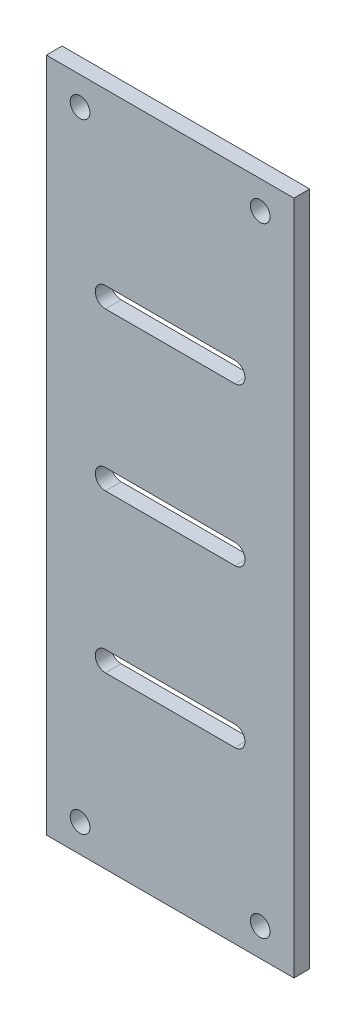
SolidWorks part; units mm, degrees
ref_plane "Front Plane" through (0, 0, 0) normal (0, 0, 1) x (1, 0, 0)
ref_plane "Top Plane" through (0, 0, 0) normal (0, 1, 0) x (1, 0, 0)
ref_plane "Right Plane" through (0, 0, 0) normal (1, 0, 0) x (0, 0, -1)
sketch "Pack access with strap ventilation profile" plane through (0, 0, 0) normal (0, 0, 1) x (1, 0, 0)
  line L0 (-22, -60) -> (22, -60)
  line L1 (22, -60) -> (22, 60)
  line L2 (22, 60) -> (-22, 60)
  line L3 (-22, 60) -> (-22, -60)
  line L4 (-11.5, -29.8) -> (11.5, -29.8)
  line L5 (11.5, -26.2) -> (-11.5, -26.2)
  line L6 (-11.5, -1.8) -> (11.5, -1.8)
  line L7 (11.5, 1.8) -> (-11.5, 1.8)
  line L8 (-11.5, 26.2) -> (11.5, 26.2)
  line L9 (11.5, 29.8) -> (-11.5, 29.8)
  circle A0 centre (-16, -55) radius 1.75
  circle A1 centre (-16, 55) radius 1.75
  circle A2 centre (16, -55) radius 1.75
  circle A3 centre (16, 55) radius 1.75
  arc A4 (11.5, -29.8) -> (11.5, -26.2) centre (11.5, -28) ccw
  arc A5 (-11.5, -26.2) -> (-11.5, -29.8) centre (-11.5, -28) ccw
  arc A6 (11.5, -1.8) -> (11.5, 1.8) centre (11.5, 0) ccw
  arc A7 (-11.5, 1.8) -> (-11.5, -1.8) centre (-11.5, 0) ccw
  arc A8 (11.5, 26.2) -> (11.5, 29.8) centre (11.5, 28) ccw
  arc A9 (-11.5, 29.8) -> (-11.5, 26.2) centre (-11.5, 28) ccw
extrude "Pack access with strap ventilation" add sketch "Pack access with strap ventilation profile" along normal blind 2.8
